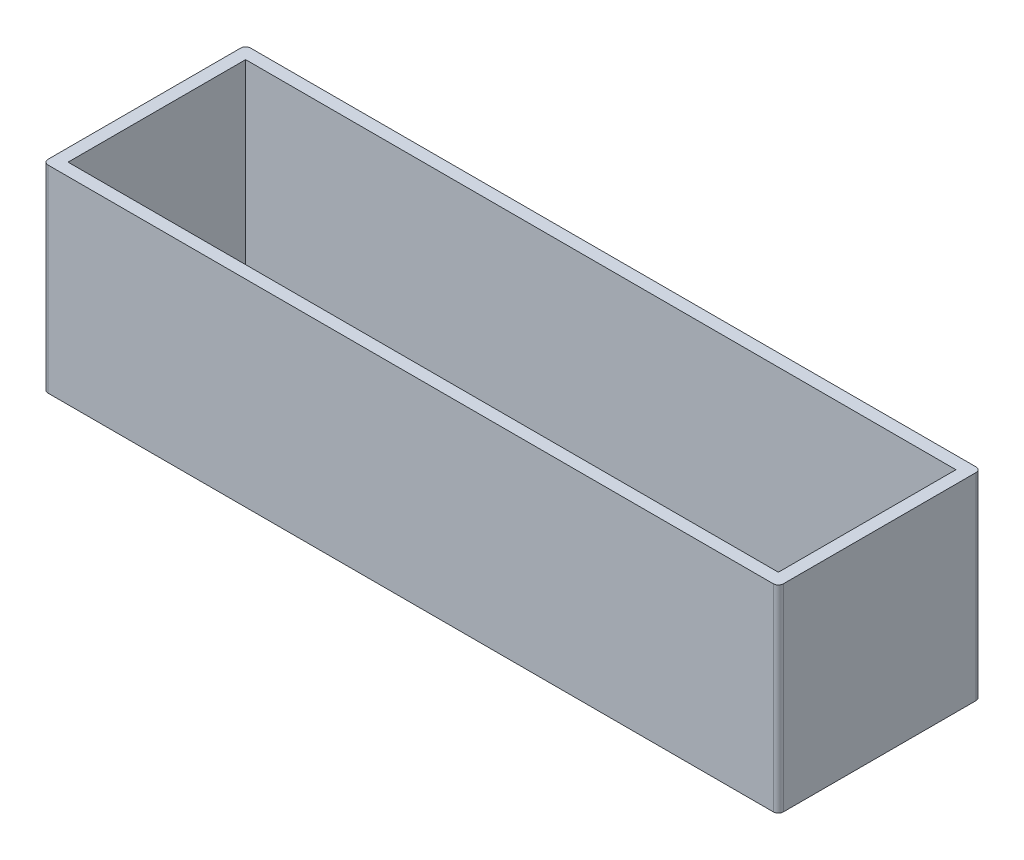
SolidWorks part; units mm, degrees
ref_plane "Front Plane" through (0, 0, 0) normal (0, 0, 1) x (1, 0, 0)
ref_plane "Top Plane" through (0, 0, 0) normal (0, 1, 0) x (1, 0, 0)
ref_plane "Right Plane" through (0, 0, 0) normal (1, 0, 0) x (0, 0, -1)
sketch "Sketch1" plane through (0, 0, 0) normal (0, 1, 0) x (1, 0, 0)
  line L1 (142, -35.5) -> (-142, -35.5)
  line L2 (142, -35.5) -> (142, 35.5)
  line L3 (142, 35.5) -> (-142, 35.5)
  line L4 (-142, -35.5) -> (-142, 35.5)
  line L5 (142, -35.5) -> (-142, 35.5) construction
  line L6 (142, 35.5) -> (-142, -35.5) construction
  line L7 (147, -40.5) -> (-147, -40.5)
  line L8 (147, -40.5) -> (147, 40.5)
  line L9 (147, 40.5) -> (-147, 40.5)
  line L10 (-147, -40.5) -> (-147, 40.5)
  line L11 (147, -40.5) -> (-147, 40.5) construction
  line L12 (147, 40.5) -> (-147, -40.5) construction
  point P0 (0, 0)
  point P6 (0, 0)
  dimension "D1" = 284
  dimension "D2" = 71
  dimension "D3" = 294
  dimension "D4" = 81
extrude "Boss-Extrude1" add sketch "Sketch1" along normal blind 79
fillet "Fillet1" radius 2 4 edges at (147, 39.5, 40.5) (147, 39.5, -40.5) (-147, 39.5, 40.5) (-147, 39.5, -40.5)
chamfer "Chamfer1" distance 2 angle 60 4 edges at (-142, 0, 0) (0, 0, -35.5) (142, 0, 0) (0, 0, 35.5)
